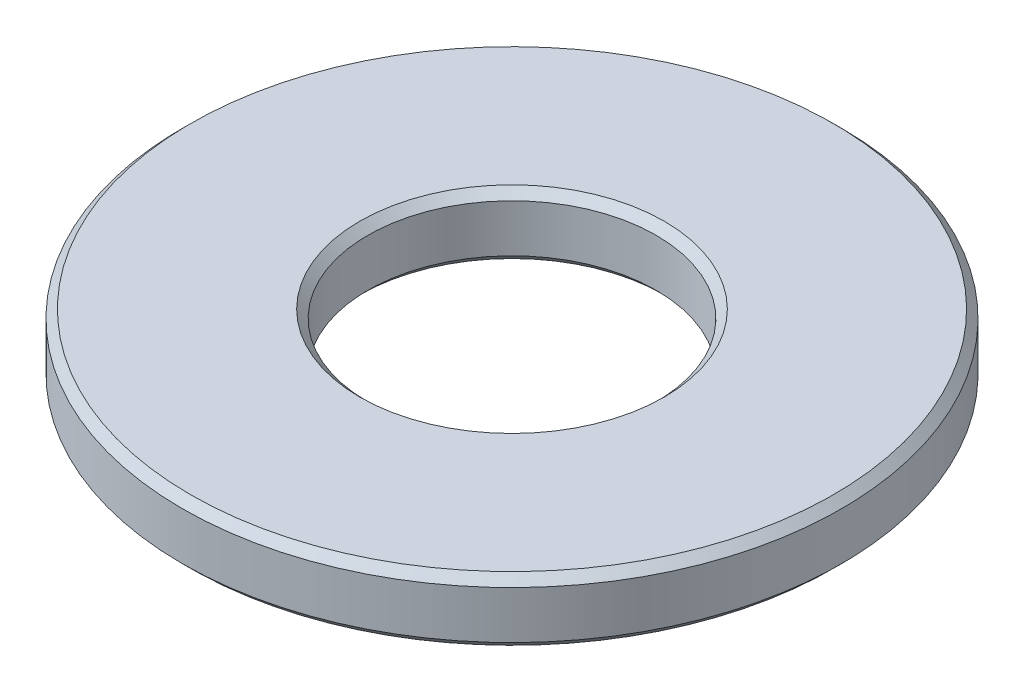
SolidWorks part; units mm, degrees
material "Alloy Steel"
ref_plane "Front Plane" through (0, 0, 0) normal (0, 0, 1) x (1, 0, 0)
ref_plane "Top Plane" through (0, 0, 0) normal (0, 1, 0) x (1, 0, 0)
ref_plane "Right Plane" through (0, 0, 0) normal (1, 0, 0) x (0, 0, -1)
ref_plane "Plane1" through (0, 0, 0) normal (0, 0, -1) x (-1, 0, 0)
sketch "Sketch1" plane through (0, 0, 0) normal (0, 0, -1) x (-1, 0, 0)
  line L0 (-8.128, 0) -> (-8.128, -1.5748)
  line L1 (-8.128, -1.5748) -> (-3.556, -1.5748)
  line L2 (-3.556, -1.5748) -> (-3.556, 0)
  line L3 (-3.556, 0) -> (-8.128, 0)
  line L4 (0, -1.5748) -> (0, 0) construction
revolve "Revolve1" add sketch "Sketch1" angle 360 about L4
chamfer "Chamfer1" distance 0.2 angle 45 4 edges at (0, -1.5748, 3.556) (0, 0, 3.556) (0, 0, 8.128) (0, -1.5748, 8.128)
